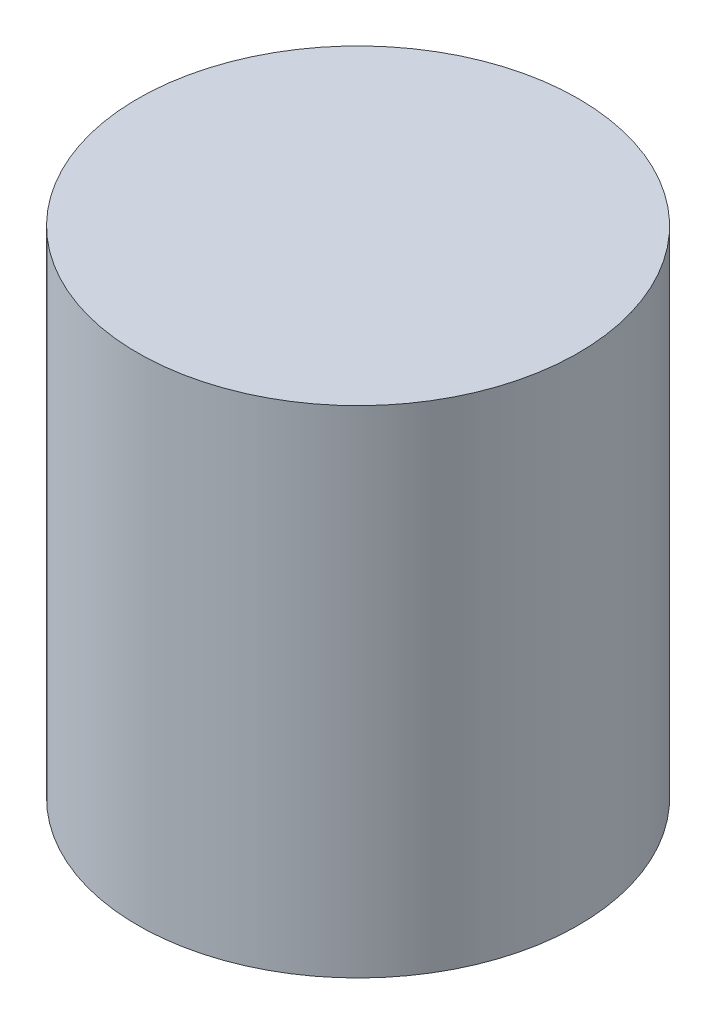
SolidWorks part; units mm, degrees
ref_plane "Front Plane" through (0, 0, 0) normal (0, 0, 1) x (1, 0, 0)
ref_plane "Top Plane" through (0, 0, 0) normal (0, 1, 0) x (1, 0, 0)
ref_plane "Right Plane" through (0, 0, 0) normal (1, 0, 0) x (0, 0, -1)
sketch "Sketch2" plane through (0, 0, 0) normal (0, 1, 0) x (1, 0, 0)
  circle A0 centre (0, 0) radius 20
  dimension "D1" = 40
extrude "Boss-Extrude1" add sketch "Sketch2" along normal blind 45
